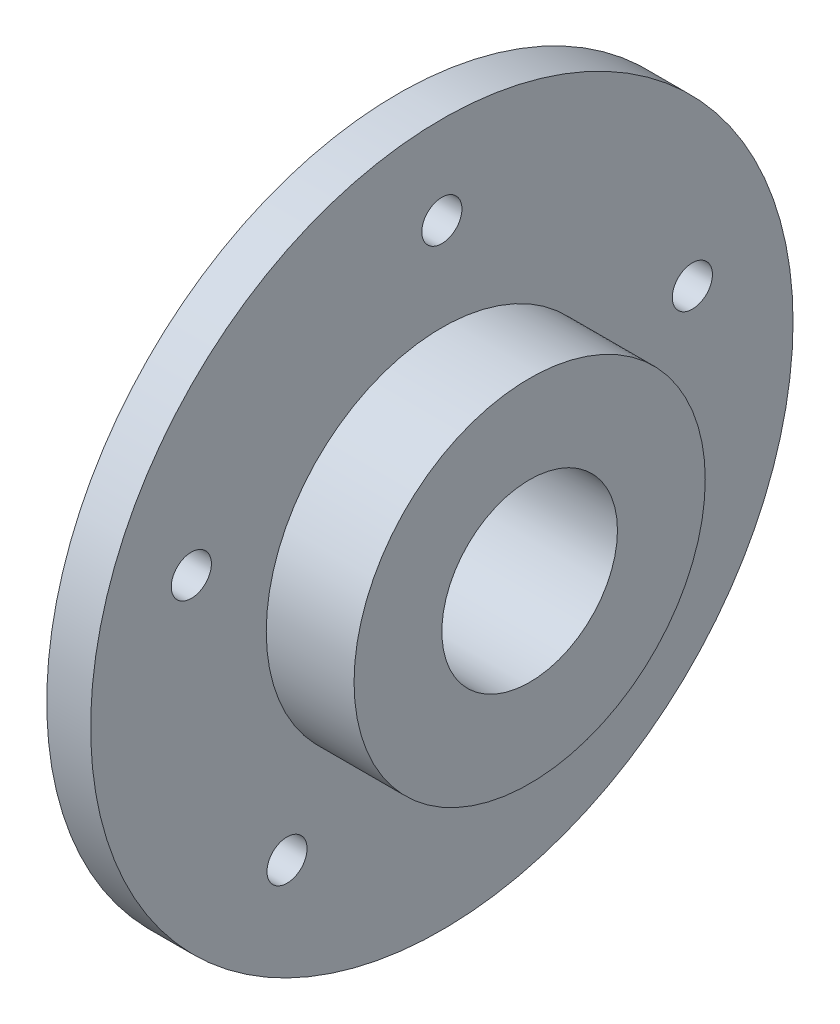
SolidWorks part; units mm, degrees
ref_plane "Front Plane" through (0, 0, 0) normal (0, 0, 1) x (1, 0, 0)
ref_plane "Top Plane" through (0, 0, 0) normal (0, 1, 0) x (1, 0, 0)
ref_plane "Right Plane" through (0, 0, 0) normal (1, 0, 0) x (0, 0, -1)
sketch "Sketch1" plane through (0, 0, 0) normal (1, 0, 0) x (0, 0, -1)
  line L0 (-36.2353, 12.4848) -> (0, 0.7113) construction
  line L1 (0, 0.7113) -> (36.2353, 12.4848) construction
  line L2 (0, 38.8113) -> (0, 0.7113) construction
  line L3 (0, 0.7113) -> (22.3946, -30.1122) construction
  line L4 (-22.3946, -30.1122) -> (0, 0.7113) construction
  circle A0 centre (0, 0.7113) radius 25.4 construction
  circle A1 centre (-36.2353, 12.4848) radius 2.9
  circle A2 centre (-22.3946, -30.1122) radius 2.9
  circle A3 centre (22.3946, -30.1122) radius 2.9
  circle A4 centre (36.2353, 12.4848) radius 2.9
  circle A5 centre (0, 38.8113) radius 2.9
  circle A6 centre (0, 0.7113) radius 50.8
  circle A7 centre (0, 0.7113) radius 38.1 construction
  dimension "D2" = 5.8
  dimension "D3" = 50.8
  dimension "D4" = 101.6
  dimension "D1" = 38.1
  dimension "D5" = 72
  dimension "D6" = 72
  dimension "D7" = 72
  dimension "D8" = 72
  dimension "D9" = 72
extrude "Boss-Extrude1" add sketch "Sketch1" along normal blind 6.35
sketch "Sketch2" plane through (6.35, 0, 0) normal (1, 0, 0) x (0, 0, -1)
  circle A0 centre (0, 0) radius 25.4
  dimension "D1" = 50.8
extrude "Boss-Extrude2" add sketch "Sketch2" along normal blind 12.7
sketch "Sketch3" plane through (19.05, 0, 0) normal (1, 0, 0) x (0, 0, -1)
  circle A0 centre (0, 0) radius 12.7
  dimension "D1" = 25.4
extrude "Cut-Extrude1" cut sketch "Sketch3" against normal up to surface (19.05 mm away) up to face at (0, 0.7113, -50.8)
